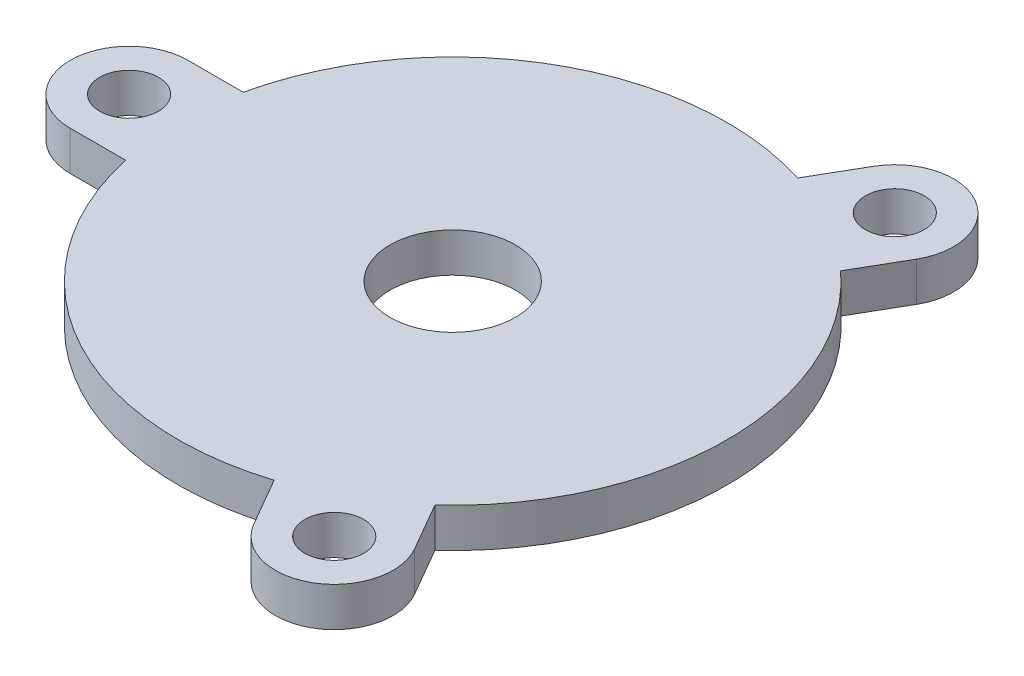
SolidWorks part; units mm, degrees
ref_plane "前视基准面" through (0, 0, 0) normal (0, 0, 1) x (1, 0, 0)
ref_plane "上视基准面" through (0, 0, 0) normal (0, 1, 0) x (1, 0, 0)
ref_plane "右视基准面" through (0, 0, 0) normal (1, 0, 0) x (0, 0, -1)
sketch "草图1" plane through (0, 0, 0) normal (0, 1, 0) x (1, 0, 0)
  line L0 (-16.5, -3) -> (-13.6748, -3)
  line L1 (-16.5, 3) -> (-13.6748, 3)
  line L2 (10.8481, 12.7894) -> (9.4355, 10.3427)
  line L3 (5.6519, 15.7894) -> (4.2393, 13.3427)
  line L4 (5.6519, -15.7894) -> (4.2393, -13.3427)
  line L5 (10.8481, -12.7894) -> (9.4355, -10.3427)
  circle A0 centre (0, 0) radius 16.5 construction
  circle A1 centre (0, 0) radius 3.2
  circle A2 centre (-16.5, 0) radius 1.5
  arc A6 (-16.2273, 2.9876) -> (-16.2273, -2.9876) centre (-16.5, 0) ccw
  arc A11 (-13.6748, -3) -> (4.2393, -13.3427) centre (0, 0) ccw
  circle A12 centre (8.25, 14.2894) radius 1.5
  arc A13 (10.701, 12.5594) -> (5.5263, 15.547) centre (8.25, 14.2894) ccw
  circle A14 centre (8.25, -14.2894) radius 1.5
  arc A15 (5.5263, -15.547) -> (10.701, -12.5594) centre (8.25, -14.2894) ccw
  arc A16 (4.2393, 13.3427) -> (-13.6748, 3) centre (0, 0) ccw
  arc A17 (9.4355, -10.3427) -> (9.4355, 10.3427) centre (0, 0) ccw
  point P13 (0, 0)
  point P17 (0, 0)
  point P32 (0, 0)
  dimension "D1" = 33
  dimension "D2" = 3
  dimension "D4" = 6.4
  dimension "D3" = 6
  dimension "D6" = 28
  dimension "D5" = 3
extrude "凸台-拉伸1" add sketch "草图1" along normal blind 2
